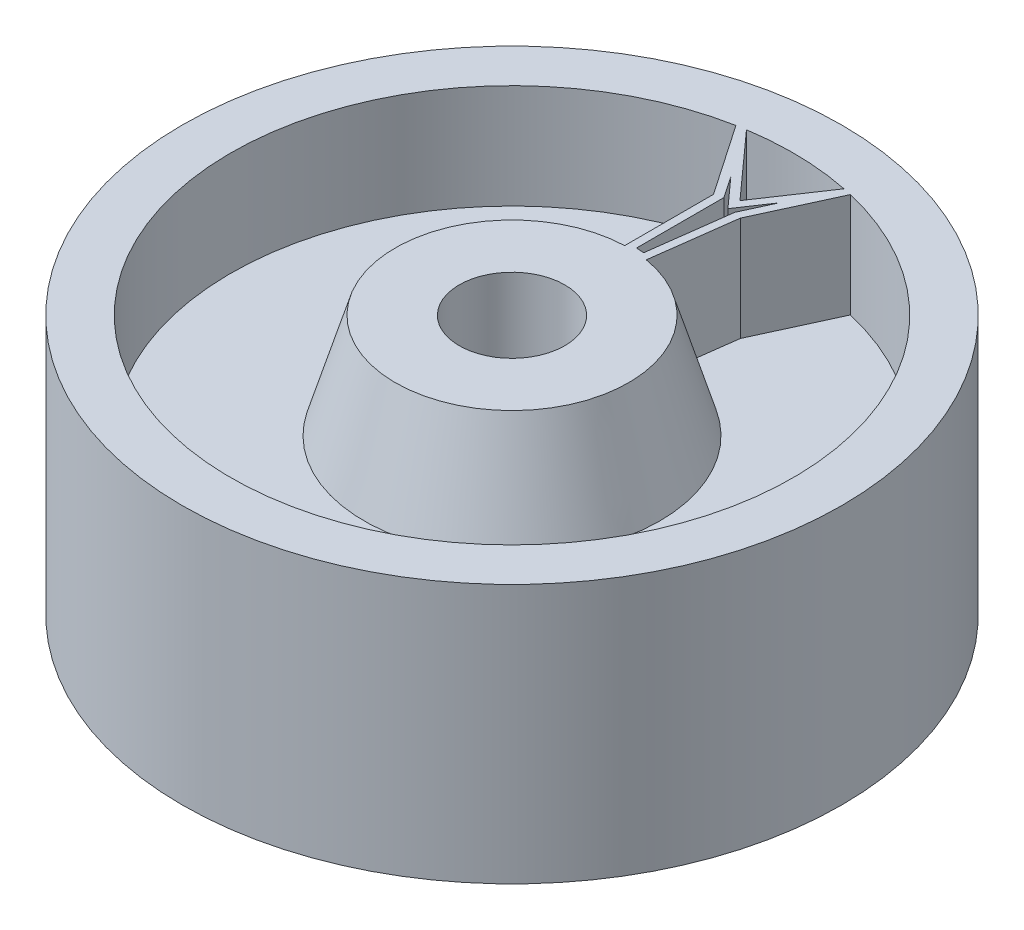
SolidWorks part; units mm, degrees
ref_plane "Front Plane" through (0, 0, 0) normal (0, 0, 1) x (1, 0, 0)
ref_plane "Top Plane" through (0, 0, 0) normal (0, 1, 0) x (1, 0, 0)
ref_plane "Right Plane" through (0, 0, 0) normal (1, 0, 0) x (0, 0, -1)
sketch "Sketch2" plane through (0, 0, 0) normal (0, 0, 1) x (1, 0, 0)
  line L0 (0, 0) -> (-556.5889, 0) construction
  line L1 (-83.8259, -205.9519) -> (-83.8259, 205.9519)
  line L2 (-83.8259, 205.9519) -> (-185.4259, 205.9519)
  line L3 (-185.4259, 205.9519) -> (-234.7577, 40.338)
  line L4 (-234.7577, 40.338) -> (-446.767, 40.338)
  line L5 (-446.767, 40.338) -> (-446.767, 205.9519)
  line L6 (-446.767, 205.9519) -> (-523.7011, 205.9519)
  line L7 (-523.7011, 205.9519) -> (-523.7011, -205.9519)
  line L8 (-234.7577, -40.338) -> (-446.767, -40.338)
  line L9 (-185.4259, -205.9519) -> (-234.7577, -40.338)
  line L10 (-83.8259, -205.9519) -> (-185.4259, -205.9519)
  line L11 (-446.767, -205.9519) -> (-523.7011, -205.9519)
  line L12 (-446.767, -40.338) -> (-446.767, -205.9519)
  line L13 (0, 0) -> (0, 242.4212) construction
  point P12 (-523.7011, 0)
  point P13 (-83.8259, 0)
revolve "Revolve2" add sketch "Sketch2" angle 360 about L13
sketch "Sketch6" plane through (0, 205.9519, 0) normal (0, 1, 0) x (1, 0, 0)
  line L0 (-234.7577, 0) -> (-446.767, 0)
  circle A0 centre (0, 0) radius 234.7577 construction
  circle A1 centre (0, 0) radius 446.767 construction
sketch "Sketch15" plane through (0, 205.9519, 0) normal (0, 1, 0) x (1, 0, 0)
  line L0 (0, 185.4259) -> (0, 328.4387)
  line L1 (0, 328.4387) -> (-76.4319, 440.1805)
  line L2 (-76.4319, 440.1805) -> (24.0661, 328.4387)
  line L3 (24.0661, 328.4387) -> (96.3579, 436.2521)
  line L4 (96.3579, 436.2521) -> (41.491, 316.7548)
  line L5 (41.491, 316.7548) -> (24.0828, 183.8554)
  line L6 (24.0828, 183.8554) -> (0, 185.4259)
  circle A0 centre (0, 0) radius 185.4259 construction
  circle A1 centre (0, 0) radius 446.767 construction
rib "Rib3" sketch "Sketch15" sketch "Sketch15" thickness 12.7 extrusion direction normal to sketch draft on no parameters "D1"=12.7
